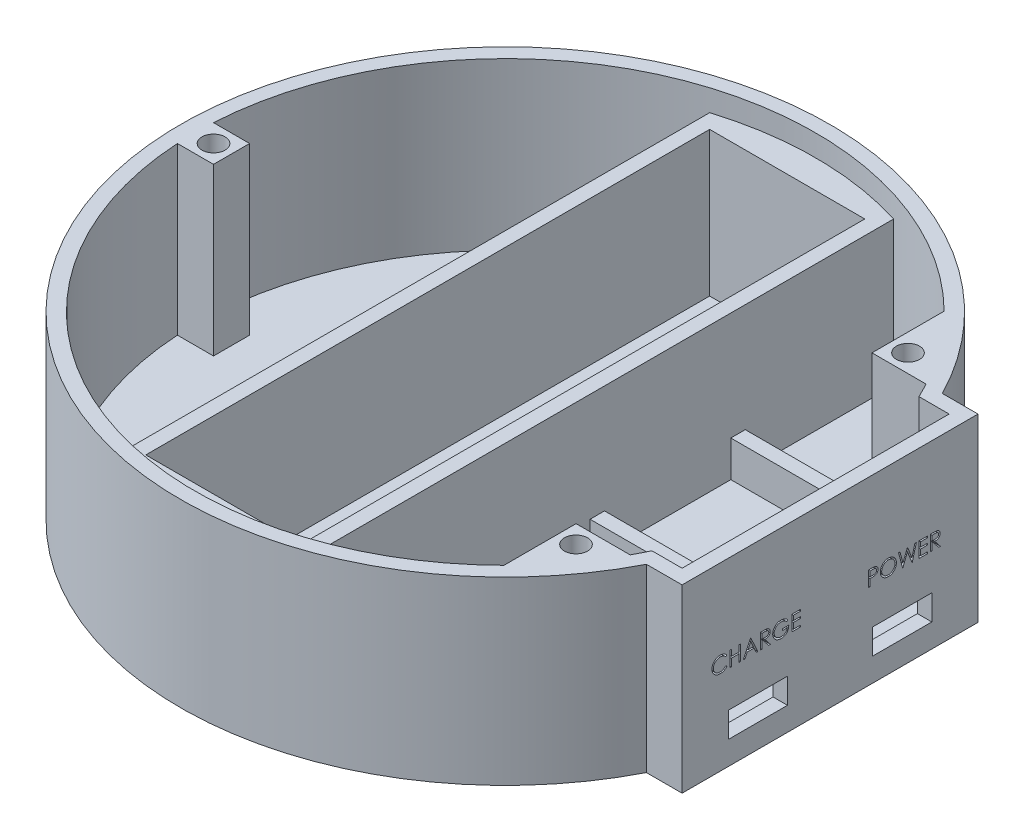
SolidWorks part; units mm, degrees
ref_plane "Front Plane" through (0, 0, 0) normal (0, 0, 1) x (1, 0, 0)
ref_plane "Top Plane" through (0, 0, 0) normal (0, 1, 0) x (1, 0, 0)
ref_plane "Right Plane" through (0, 0, 0) normal (1, 0, 0) x (0, 0, -1)
sketch "Sketch1" plane through (0, 0, 0) normal (0, 1, 0) x (1, 0, 0)
  line L1 (40.0593, 20.5) -> (45, 20.5)
  line L3 (40.0593, -20.5) -> (45, -20.5)
  line L4 (45, 20.5) -> (45, -20.5)
  arc A0 (40.0593, 20.5) -> (40.0593, -20.5) centre (0, 0) ccw
  dimension "D1" = 90
  dimension "D2" = 41
extrude "Body" add sketch "Sketch1" along normal blind 25
shell "Shell1" thickness 2
sketch "Sketch2" plane through (0, 2, 0) normal (0, 1, 0) x (1, 0, 0)
  line L4 (-10.75, -39.0663) -> (-10.75, 39.0663)
  line L8 (-12.75, -41.0663) -> (-12.75, 41.0663)
  line L9 (12.75, -41.0663) -> (-12.75, 41.0663) construction
  line L10 (12.75, 41.0663) -> (-12.75, -41.0663) construction
  line L11 (10.75, 39.0663) -> (-10.75, 39.0663)
  line L12 (10.75, -39.0663) -> (10.75, 39.0663)
  line L13 (10.75, -39.0663) -> (-10.75, -39.0663)
  line L14 (12.75, 41.0663) -> (-12.75, 41.0663) construction
  line L15 (12.75, -41.0663) -> (-12.75, -41.0663) construction
  line L23 (12.75, -41.0663) -> (12.75, 41.0663) construction
  line L24 (-1000, 0) -> (49000, 0) construction
  line L29 (12.75, 41.0663) -> (12.75, -41.0663)
  circle A0 centre (0, 0) radius 43 construction
  arc A5 (38.8169, 18.5) -> (38.8169, -18.5) centre (0, 0) ccw construction
  arc A7 (-12.75, -41.0663) -> (12.75, -41.0663) centre (0, 0) ccw
  arc A8 (12.75, 41.0663) -> (-12.75, 41.0663) centre (0, 0) ccw
  arc A9 (38.8169, 18.5) -> (38.8169, -18.5) centre (0, 0) ccw construction
  dimension "D1" = 2
  dimension "D2" = 21.5
extrude "Battery_Case" add sketch "Sketch2" along normal blind 20
sketch "Sketch3" plane through (45, 0, 0) normal (1, 0, 0) x (0, 0, -1)
  line L0 (0, -1000) -> (0, 49000) construction
  line L1 (-14.1, 6.75) -> (-5.9, 6.75)
  line L2 (-14.1, 6.75) -> (-14.1, 3.25)
  line L3 (-14.1, 3.25) -> (-5.9, 3.25)
  line L4 (-5.9, 6.75) -> (-5.9, 3.25)
  line L5 (-14.1, 6.75) -> (-5.9, 3.25) construction
  line L6 (-14.1, 3.25) -> (-5.9, 6.75) construction
  line L7 (5.9, 6.75) -> (5.9, 3.25)
  line L8 (14.1, 3.25) -> (5.9, 3.25)
  line L9 (14.1, 6.75) -> (14.1, 3.25)
  line L10 (14.1, 6.75) -> (5.9, 6.75)
  point P0 (-10, 5)
  dimension "D1" = 8.2
  dimension "D2" = 3.5
  dimension "D3" = 10
  dimension "D4" = 5
extrude "USB_Hole" cut sketch "Sketch3" against normal up to next
sketch "Sketch4" plane through (0, 2, 0) normal (0, 1, 0) x (1, 0, 0)
  line L0 (38.8169, 18.5) -> (12.75, 18.5)
  line L1 (12.75, -41.0663) -> (12.75, 41.0663) construction
  line L2 (12.75, 18.5) -> (12.75, 20.5)
  line L3 (12.75, 20.5) -> (37.7988, 20.5)
  line L4 (-1000, 0) -> (49000, 0) construction
  line L5 (38.8169, -18.5) -> (12.75, -18.5)
  line L6 (12.75, -18.5) -> (12.75, -20.5)
  line L7 (12.75, -20.5) -> (37.7988, -20.5)
  line L8 (43, -18.5) -> (43, 18.5) construction
  line L9 (43, 1) -> (12.75, 1)
  line L10 (43, 1) -> (43, -1)
  line L11 (43, -1) -> (12.75, -1)
  line L12 (12.75, 1) -> (12.75, -1)
  line L13 (12.75, -41.0663) -> (12.75, 41.0663) construction
  arc A0 (38.8169, 18.5) -> (12.75, 41.0663) centre (0, 0) ccw construction
  arc A1 (12.75, -41.0663) -> (38.8169, -18.5) centre (0, 0) ccw construction
  arc A2 (37.7988, -20.5) -> (38.8169, -18.5) centre (0, 0) ccw
  arc A3 (38.8169, 18.5) -> (37.7988, 20.5) centre (0, 0) ccw
  dimension "D1" = 2
  dimension "D2" = 1
extrude "PCB_Place" add sketch "Sketch4" along normal blind 5
sketch "Sketch5" plane through (0, 2, 0) normal (0, 1, 0) x (1, 0, 0)
  line L0 (-42.9273, 2.5) -> (-37.9273, -2.5) construction
  line L1 (-42.9273, 2.5) -> (-37.9273, 2.5)
  line L2 (-42.9273, 2.5) -> (-42.9273, -2.5) construction
  line L3 (-42.9273, -2.5) -> (-37.9273, -2.5)
  line L4 (-37.9273, 2.5) -> (-37.9273, -2.5)
  line L5 (-1000, 0) -> (49000, 0) construction
  line L6 (37.7988, 20.5) -> (30.3109, 20.5)
  line L9 (30.3109, 20.5) -> (30.3109, 30.5)
  line L11 (37.7988, -20.5) -> (30.3109, -20.5)
  line L13 (30.3109, -20.5) -> (30.3109, -30.5)
  arc A0 (-12.75, 41.0663) -> (-12.75, -41.0663) centre (0, 0) ccw construction
  arc A2 (38.8169, 18.5) -> (38.8169, -18.5) centre (0, 0) ccw construction
  circle A3 centre (-40.4273, 0) radius 1.6
  circle A4 centre (32.7988, 23) radius 1.6
  arc A5 (37.7988, 20.5) -> (12.75, 41.0663) centre (0, 0) ccw construction
  circle A6 centre (32.7988, -23) radius 1.6
  arc A7 (37.7988, 20.5) -> (30.3109, 30.5) centre (0, 0) ccw
  arc A8 (-42.9273, 2.5) -> (-42.9273, -2.5) centre (0, 0) ccw
  arc A9 (30.3109, -30.5) -> (37.7988, -20.5) centre (0, 0) ccw
  dimension "D3" = 3.2
  dimension "D1" = 5
  dimension "D2" = 5
  dimension "D4" = 5
  dimension "D5" = 2.5
  dimension "D6" = 10
extrude "Fixation_Hole" add sketch "Sketch5" along normal up to surface (23 mm away)
sketch "Sketch6" plane through (45, 0, 0) normal (1, 0, 0) x (0, 0, -1)
  line L0 (-20.5, 11.75) -> (0, 11.75) construction
  line L1 (-20.5, 25) -> (-20.5, 0) construction
  line L4 (-5.9, 6.75) -> (-14.1, 6.75) construction
  line L5 (0, 11.75) -> (20.5, 11.75) construction
  line L6 (20.5, 25) -> (20.5, 0) construction
  text T0 "CHARGE" font "Century Gothic" height in points 8
  text T1 "POWER" font "Century Gothic" height in points 8
  dimension "D1" = 5
extrude "Cut-Extrude2" cut sketch "Sketch6" against normal blind 1
